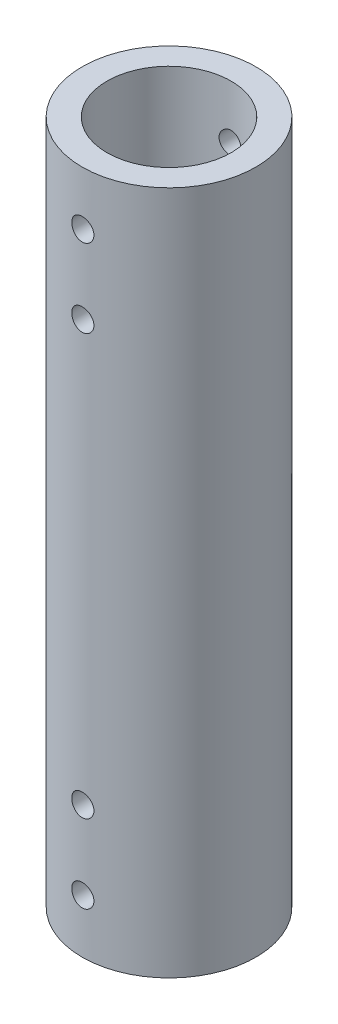
SolidWorks part; units mm, degrees
material "PVC Rigid"
ref_plane "Front Plane" through (0, 0, 0) normal (0, 0, 1) x (1, 0, 0)
ref_plane "Top Plane" through (0, 0, 0) normal (0, 1, 0) x (1, 0, 0)
ref_plane "Right Plane" through (0, 0, 0) normal (1, 0, 0) x (0, 0, -1)
sketch "Sketch1" plane through (0, 0, 0) normal (0, 1, 0) x (1, 0, 0)
  circle A0 centre (0, 0) radius 13.335
  circle A1 centre (0, 0) radius 9.525
  dimension "D1" = 26.67
  dimension "D2" = 19.05
extrude "Boss-Extrude1" add sketch "Sketch1" along normal blind 105
sketch "Sketch4" plane through (0, 0, 0) normal (0, 0, 1) x (1, 0, 0)
  line L0 (0, 105) -> (0, 84.7442) construction
  line L1 (9.525, 105) -> (-9.525, 105) construction
  line L2 (13.335, 105) -> (-13.335, 105) construction
  circle A0 centre (0, 96.7442) radius 1.7
  circle A1 centre (0, 84.7442) radius 1.7
  circle A3 centre (0, 84.7442) radius 1.7 construction
  point P2 (0, 0)
  point P4 (0, 79.9644)
  point P6 (7.2712, 91.7442)
  dimension "D1" = 3.4
  dimension "D2" = 3.4
  dimension "D3" = 8.2558
  dimension "D4" = 12
extrude "Cut-Extrude1" cut sketch "Sketch4" against normal through all both and the other way through all
sketch "Sketch6" plane through (0, 0, 0) normal (0, 0, 1) x (1, 0, 0)
  line L0 (13.335, 105) -> (13.335, 0) construction
  line L1 (13.335, 105) -> (-13.335, 105) construction
  line L2 (-13.335, 0) -> (13.335, 0) construction
  line L3 (13.335, 52.5) -> (-13.335, 52.5) construction
  line L4 (-13.335, 105) -> (-13.335, 0) construction
  line L5 (13.335, 0) -> (13.335, 105) construction
  point P10 (0, 0)
  point P11 (34.4785, 0)
ref_plane "Plane2" through (0, 52.5, 0) normal (0, 1, 0) x (1, 0, 0)
mirror "Mirror2" about plane through (0, 52.5, 0) normal (0, 1, 0) of "Cut-Extrude1"
